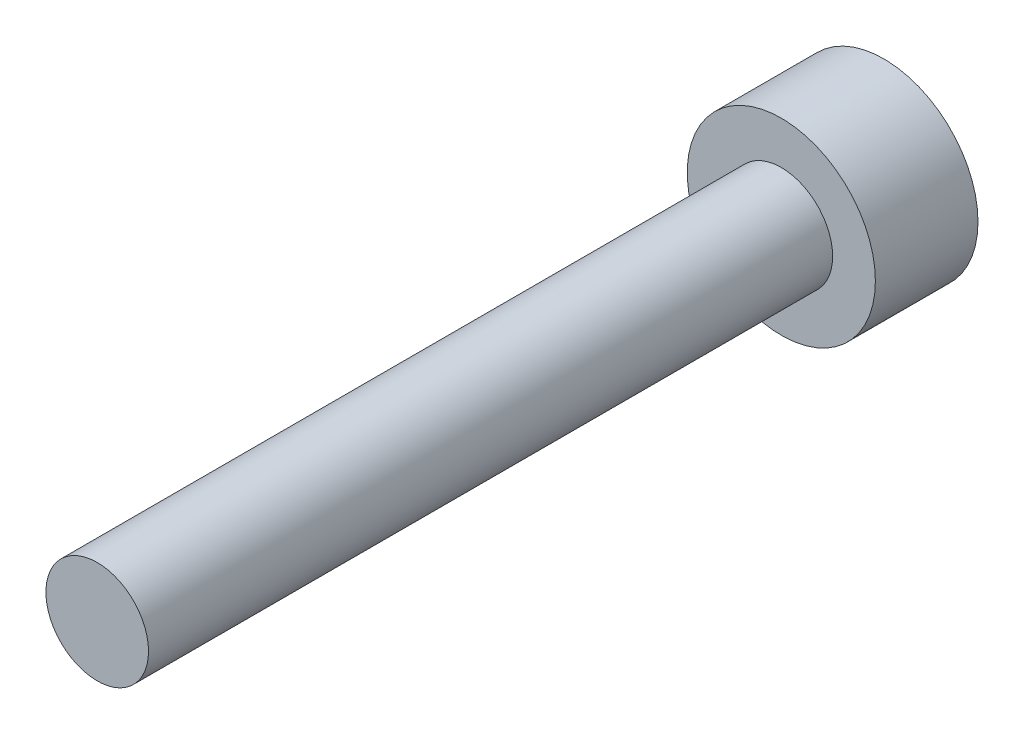
SolidWorks part; units mm, degrees
ref_plane "Plano frontal" through (0, 0, 0) normal (0, 0, 1) x (1, 0, 0)
ref_plane "Plano superior" through (0, 0, 0) normal (0, 1, 0) x (1, 0, 0)
ref_plane "Plano direito" through (0, 0, 0) normal (1, 0, 0) x (0, 0, -1)
sketch "Esboço1" plane through (0, 0, 0) normal (0, 0, 1) x (1, 0, 0)
  circle A0 centre (0, 0) radius 2.75
  dimension "D1" = 5.5
extrude "Ressalto-extrusão1" add sketch "Esboço1" along normal blind 3
sketch "Esboço2" plane through (0, 0, 3) normal (0, 0, 1) x (1, 0, 0)
  circle A0 centre (0, 0) radius 1.5
  dimension "D1" = 3
extrude "Ressalto-extrusão2" add sketch "Esboço2" along normal blind 20
